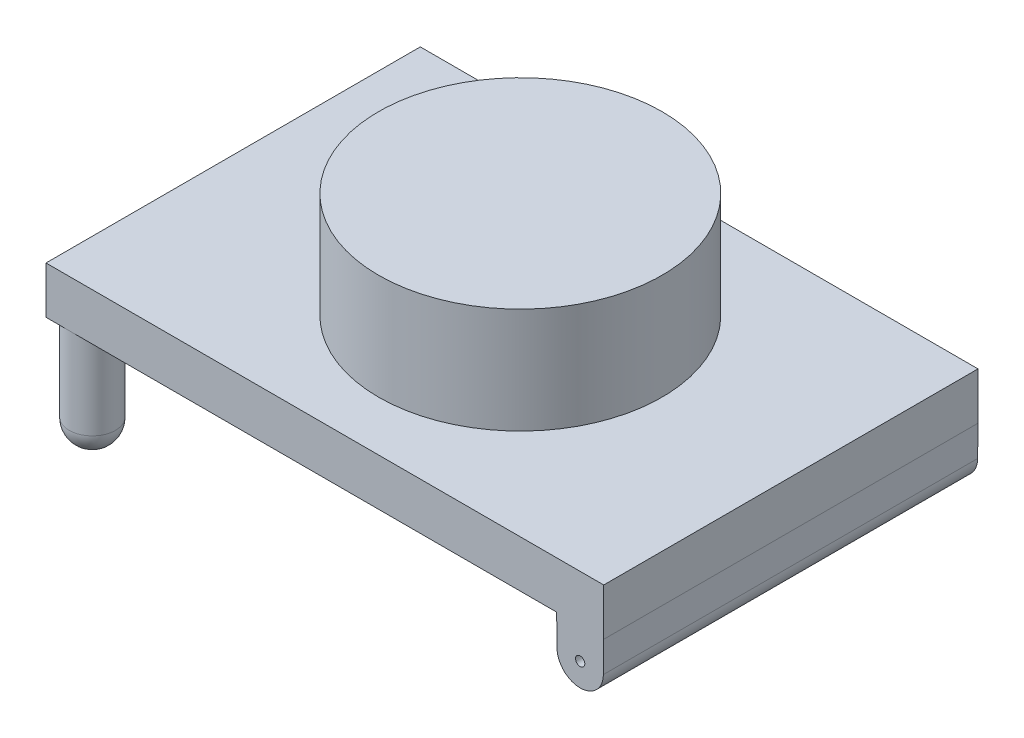
SolidWorks part; units mm, degrees
ref_plane "Front Plane" through (0, 0, 0) normal (0, 0, 1) x (1, 0, 0)
ref_plane "Top Plane" through (0, 0, 0) normal (0, 1, 0) x (1, 0, 0)
ref_plane "Right Plane" through (0, 0, 0) normal (1, 0, 0) x (0, 0, -1)
sketch "Sketch1" plane through (0, 0, 0) normal (0, 1, 0) x (1, 0, 0)
  line L1 (150.5, -101) -> (-150.5, -101)
  line L2 (150.5, -101) -> (150.5, 101)
  line L3 (150.5, 101) -> (-150.5, 101)
  line L4 (-150.5, -101) -> (-150.5, 101)
  line L5 (150.5, -101) -> (-150.5, 101) construction
  line L6 (150.5, 101) -> (-150.5, -101) construction
  point P0 (0, 0)
  dimension "D1" = 301
  dimension "D2" = 202
extrude "Boss-Extrude1" add sketch "Sketch1" along normal blind 60
sketch "Sketch2" plane through (0, 0, 101) normal (0, 0, 1) x (1, 0, 0)
  line L0 (-150.5, 60) -> (150.5, 60) construction
  line L1 (150.5, 60) -> (150.5, 0) construction
  circle A0 centre (137.8, 18) radius 2.5
  dimension "D1" = 5
  dimension "D2" = 42
  dimension "D3" = 12.7
sketch "Sketch4" plane through (0, 0, 101) normal (0, 0, 1) x (1, 0, 0)
  line L0 (137.8, 18) -> (137.8, 60) construction
  line L1 (125.1, 60) -> (150.5, 60)
  line L2 (125.1, 60) -> (125.1, 34.6)
  line L3 (125.1, 34.6) -> (150.5, 34.6)
  line L4 (150.5, 60) -> (150.5, 34.6)
  line L5 (-150.5, 60) -> (150.5, 60) construction
  line L6 (125.3, 18) -> (125.1, 34.6)
  line L7 (150.3, 18) -> (150.5, 34.6)
  line L8 (-150.5, 60) -> (125.1, 60)
  line L9 (-150.5, 60) -> (-150.5, 34.6)
  line L10 (-150.5, 34.6) -> (125.1, 34.6)
  line L11 (125.1, 60) -> (125.1, 34.6)
  circle A0 centre (137.8, 18) radius 12.5
  line M12 (-150.5, 0) -> (150.5, 0)
  line M13 (150.5, 0) -> (150.5, 60)
  line M15 (-150.5, 60) -> (-150.5, 0)
  dimension "D1" = 25
  dimension "D2" = 25.4
  dimension "D3" = 25.4
  dimension "D4" = 25.4
extrude "Cut-Extrude1" cut sketch "Sketch4" against normal through all contours A0 L6 L10 L7 M15 M12 M13 | L4 L1 L2
sketch "Sketch5" plane through (0, 34.6, 0) normal (0, -1, 0) x (1, 0, 0)
  line L0 (-138, 88.5) -> (-138, -88.5) construction
  line L1 (-150.5, -101) -> (-150.5, 101) construction
  line L2 (-150.5, -101) -> (125.1, -101) construction
  line L3 (-150.5, 101) -> (125.1, 101) construction
  circle A0 centre (-138, 88.5) radius 12.5
  circle A1 centre (-138, -88.5) radius 12.5
  dimension "D1" = 25
extrude "Boss-Extrude2" add sketch "Sketch5" along normal blind 59.1
fillet "Fillet1" radius 12.5 2 edges at (-138, -24.5, -101) (-138, -24.5, 76)
extrude "Cut-Extrude2" cut sketch "Sketch2" against normal through all contours A0
sketch "Sketch6" plane through (0, 60, 0) normal (0, 1, 0) x (1, 0, 0)
  line L0 (2, -74) -> (2, -101) construction
  line L1 (-150.5, -101) -> (150.5, -101) construction
  line L2 (2, 79) -> (2, 101) construction
  line L3 (150.5, 101) -> (-150.5, 101) construction
  line L4 (-74.5, 2.5) -> (-150.5, 2.5) construction
  line L5 (-150.5, 101) -> (-150.5, -101) construction
  circle A0 centre (2, 2.5) radius 76.5
  dimension "D1" = 22
  dimension "D2" = 27
  dimension "D3" = 76
extrude "Boss-Extrude3" add sketch "Sketch6" along normal blind 57
sketch "Sketch7" plane through (0, 117, 0) normal (0, 1, 0) x (1, 0, 0)
  line L1 (-150.5, -101) -> (150.5, -101) construction
  line L2 (150.5, 101) -> (-150.5, 101) construction
  line L3 (-150.5, 101) -> (-150.5, -101) construction
  circle A0 centre (-35.5, -34) radius 1.5
  circle A1 centre (-24.5, 34) radius 1.5
  dimension "D5" = 3
  dimension "D6" = 3
  dimension "D1" = 115
  dimension "D2" = 126
  dimension "D3" = 67
  dimension "D4" = 67
sketch "Sketch8" plane through (0, 60, 0) normal (0, 1, 0) x (1, 0, 0)
  line L0 (140.3, 101) -> (135.3, 101) construction
  line L1 (140.3, 101) -> (135.3, 101)
  line L2 (137.8, 101) -> (137.8, 0)
  line L3 (137.8, 0) -> (137.8, -101)
  line L4 (-150.5, -101) -> (150.5, -101) construction
